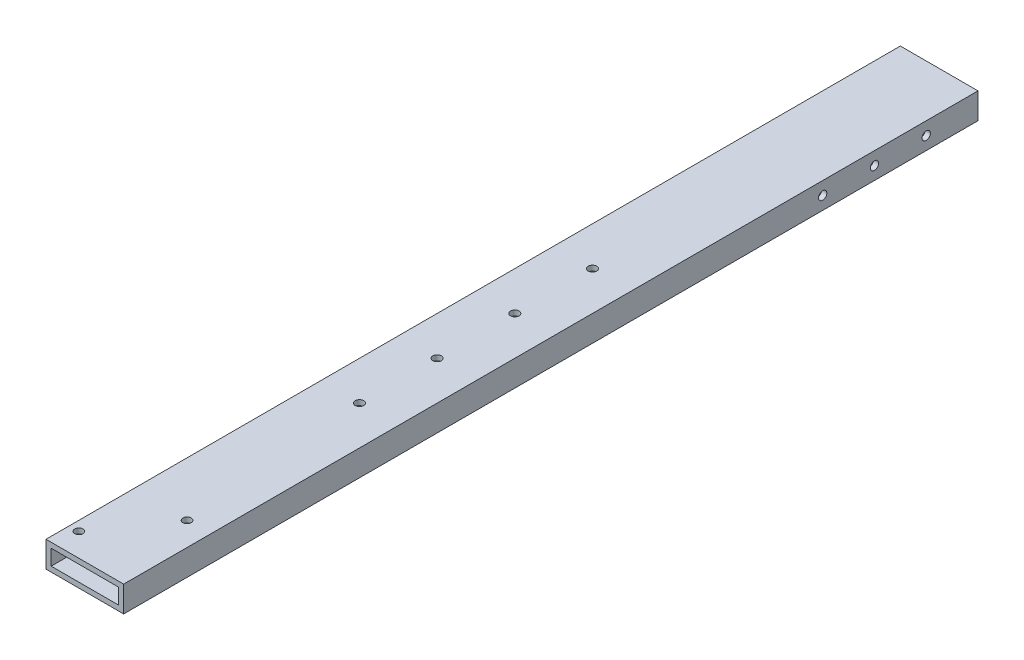
SolidWorks part; units mm, degrees
material "6061 合金"
ref_plane "前视基准面" through (0, 0, 0) normal (0, 0, 1) x (1, 0, 0)
ref_plane "上视基准面" through (0, 0, 0) normal (0, 1, 0) x (1, 0, 0)
ref_plane "右视基准面" through (0, 0, 0) normal (1, 0, 0) x (0, 0, -1)
other "Configuration Table"
sketch "草图1" plane through (0, 0, 0) normal (0, 0, 1) x (1, 0, 0)
  line L1 (-15, 5) -> (15, 5)
  line L2 (-15, 5) -> (-15, -5)
  line L3 (-15, -5) -> (15, -5)
  line L4 (15, 5) -> (15, -5)
  line L5 (-15, 5) -> (15, -5) construction
  line L6 (-15, -5) -> (15, 5) construction
  line L7 (-13, 3) -> (13, 3)
  line L8 (-13, 3) -> (-13, -3)
  line L9 (-13, -3) -> (13, -3)
  line L10 (13, 3) -> (13, -3)
  line L11 (-13, 3) -> (13, -3) construction
  line L12 (-13, -3) -> (13, 3) construction
  point P0 (0, 0)
  point P6 (0, 0)
  dimension "2" = 2
  dimension "D2" = 2
  dimension "D3" = 10
  dimension "D4" = 30
extrude "凸台-拉伸1" add sketch "草图1" along normal blind 330
sketch "草图2" plane through (0, 5, 0) normal (0, 1, 0) x (1, 0, 0)
  line L0 (-15, -330) -> (-15, 0) construction
  line L1 (15, -330) -> (-15, -330) construction
  circle A0 centre (-11.3, -321) radius 1.6
  dimension "D1" = 3.2
  dimension "D2" = 3.7
  dimension "D3" = 9
extrude "切除-拉伸1" cut sketch "草图2" against normal through all
sketch "草图3" plane through (0, 5, 0) normal (0, 1, 0) x (1, 0, 0)
  circle A0 centre (5.9073, -296.4254) radius 1.6
  circle A1 centre (5.9073, -296.4254) radius 2
  circle A2 centre (5.9073, -296.4254) radius 2 construction
  circle A3 centre (-11.3, -321) radius 2
  circle A4 centre (-11.3, -321) radius 2 construction
  circle A112 centre (0, -163.9123) radius 1.65
  circle A113 centre (0, -163.9123) radius 1.65
  circle A114 centre (0, -133.9123) radius 1.65
  circle A115 centre (0, -133.9123) radius 1.65
  circle A120 centre (0, -223.9123) radius 1.65
  circle A121 centre (0, -223.9123) radius 1.65
  circle A122 centre (0, -193.9123) radius 1.65
  circle A123 centre (0, -193.9123) radius 1.65
  dimension "D3" = 3.2
  dimension "D1" = 0
  dimension "D2" = 0
  dimension "D4" = 0
  dimension "D5" = 0
  dimension "D8" = 0
  dimension "D9" = 0
extrude "切除-拉伸2" cut sketch "草图3" against normal through all
sketch "草图4" plane through (-15, 0, 0) normal (-1, 0, 0) x (0, 0, 1)
  line L0 (20, 0) -> (40, 0) construction
  circle A0 centre (20, 0) radius 1.6
  circle A1 centre (40, 0) radius 1.6
  circle A2 centre (60, 0) radius 1.6
  dimension "D1" = 20
  dimension "D2" = 3.2
  dimension "D4" = 20
  dimension "D3" = 3
extrude "切除-拉伸3" cut sketch "草图4" against normal through all
sketch "草图5" plane through (0, 5, 0) normal (0, 1, 0) x (1, 0, 0)
  line L0 (0, -105) -> (0, -15) construction
  line L1 (-9, -105) -> (-9, -15)
  line L2 (9, -105) -> (9, -15)
  line L3 (15, -330) -> (15, 0) construction
  line L4 (15, 0) -> (-15, 0) construction
  arc A0 (-9, -105) -> (9, -105) centre (0, -105) ccw
  arc A1 (9, -15) -> (-9, -15) centre (0, -15) ccw
  point P2 (0, -60)
  dimension "D2" = 15
  dimension "D1" = 6
  dimension "D3" = 90
extrude "切除-拉伸4" [suppressed] cut sketch "草图5" against normal through all
